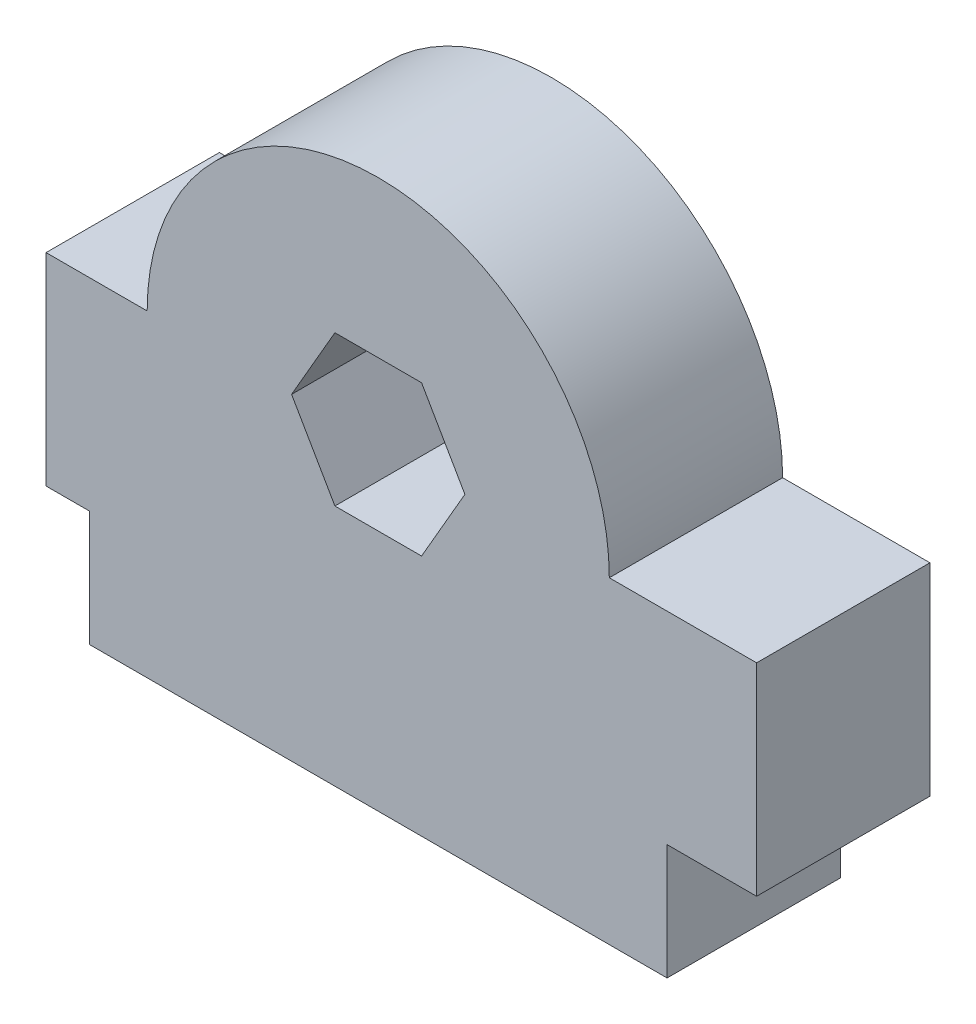
SolidWorks part; units mm, degrees
ref_plane "Front Plane" through (0, 0, 0) normal (0, 0, 1) x (1, 0, 0)
ref_plane "Top Plane" through (0, 0, 0) normal (0, 1, 0) x (1, 0, 0)
ref_plane "Right Plane" through (0, 0, 0) normal (1, 0, 0) x (0, 0, -1)
sketch "Sketch1" plane through (0, 0, 0) normal (0, 0, 1) x (1, 0, 0)
  line L0 (0, 0) -> (20, 0)
  line L1 (0, 0) -> (0, 4)
  line L2 (20, 0) -> (20, 4)
  line L3 (0, 4) -> (-1.5, 4)
  line L4 (23.1, 11) -> (23.1, 4)
  line L5 (-1.5, 4) -> (-1.5, 11)
  line L6 (-1.5, 11) -> (2, 11)
  line L7 (18, 11) -> (23.1, 11)
  line L8 (23.1, 4) -> (20, 4)
  line L11 (13, 11) -> (11.5, 13.5981)
  line L12 (11.5, 13.5981) -> (8.5, 13.5981)
  line L13 (8.5, 13.5981) -> (7, 11)
  line L14 (7, 11) -> (8.5, 8.4019)
  line L15 (8.5, 8.4019) -> (11.5, 8.4019)
  line L16 (11.5, 8.4019) -> (13, 11)
  arc A0 (18, 11) -> (2, 11) centre (10, 11) ccw
  dimension "D1" = 20
  dimension "D5" = 8
  dimension "D2" = 5.1
  dimension "D3" = 1.5
  dimension "D4" = 7
  dimension "D7" = 7
  dimension "D9" = 4
  dimension "D13" = 3.5
extrude "Boss-Extrude1" add sketch "Sketch1" along normal blind 6
